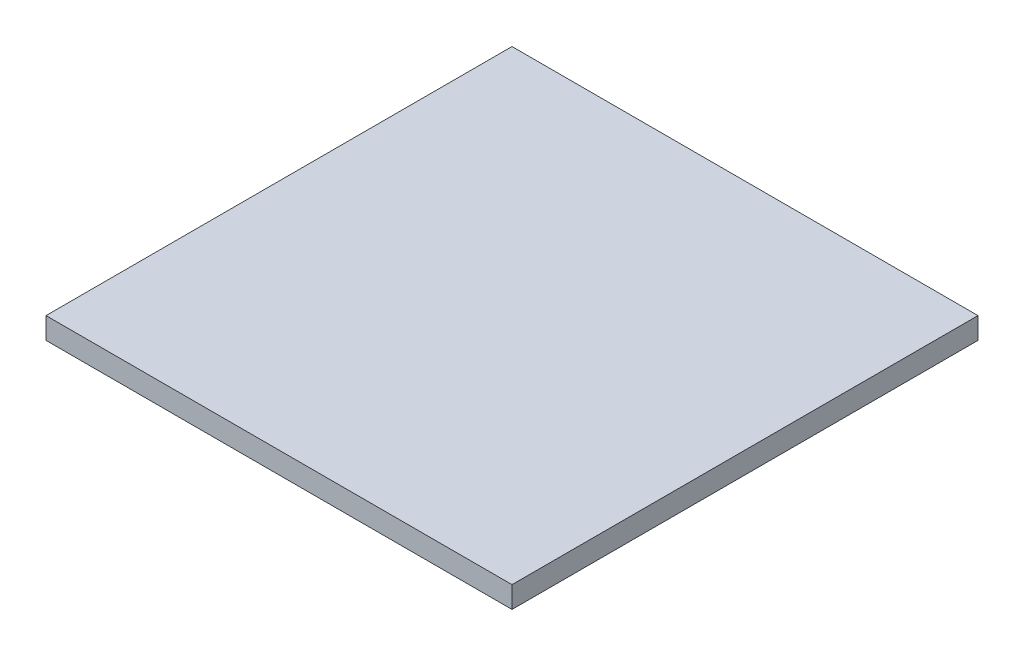
SolidWorks part; units mm, degrees
ref_plane "Спереди" through (0, 0, 0) normal (0, 0, 1) x (1, 0, 0)
ref_plane "Сверху" through (0, 0, 0) normal (0, 1, 0) x (1, 0, 0)
ref_plane "Справа" through (0, 0, 0) normal (1, 0, 0) x (0, 0, -1)
sketch "Эскиз1" plane through (0, 0, 0) normal (0, 1, 0) x (1, 0, 0)
  line L1 (-65, 65) -> (65, 65)
  line L2 (-65, 65) -> (-65, -65)
  line L3 (-65, -65) -> (65, -65)
  line L4 (65, 65) -> (65, -65)
  line L5 (-65, 65) -> (65, -65) construction
  line L6 (-65, -65) -> (65, 65) construction
  point P0 (0, 0)
extrude "Бобышка-Вытянуть1" add sketch "Эскиз1" along normal blind 6
